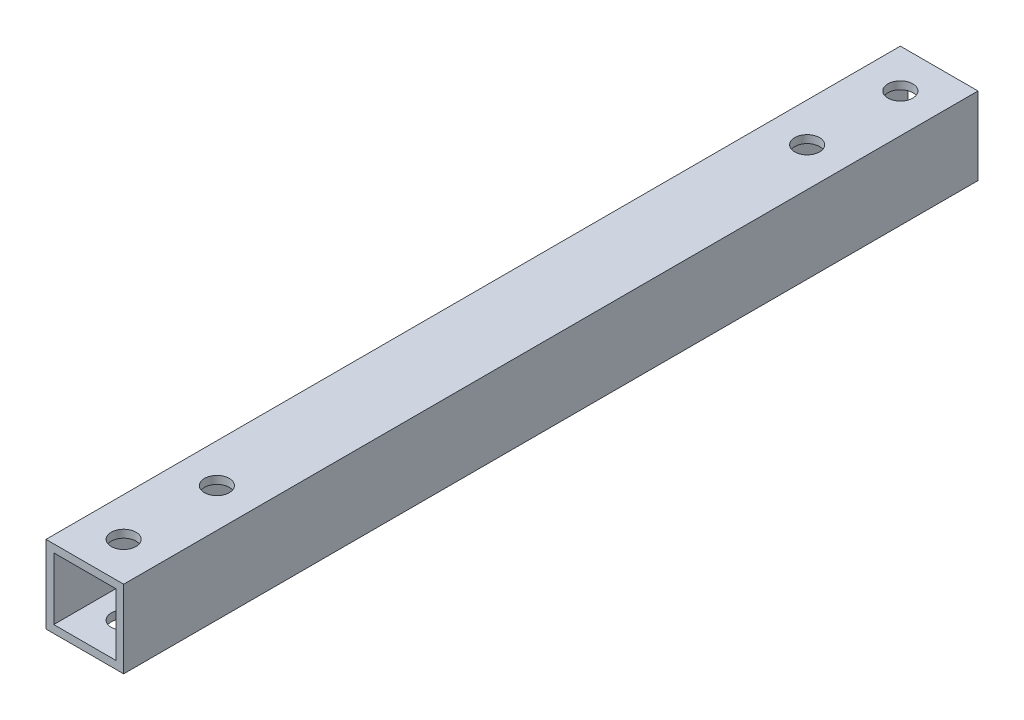
SolidWorks part; units mm, degrees
material "6061 合金"
ref_plane "正面" through (0, 0, 0) normal (0, 0, 1) x (1, 0, 0)
ref_plane "平面" through (0, 0, 0) normal (0, 1, 0) x (1, 0, 0)
ref_plane "右側面" through (0, 0, 0) normal (1, 0, 0) x (0, 0, -1)
sketch "断面 スケッチ" plane through (0, 0, 0) normal (0, 0, 1) x (1, 0, 0)
  line L1 (-5, -5) -> (5, -5)
  line L2 (-5, -5) -> (-5, 5)
  line L3 (-5, 5) -> (5, 5)
  line L4 (5, -5) -> (5, 5)
  line L5 (-5, -5) -> (5, 5) construction
  line L6 (-5, 5) -> (5, -5) construction
  point P0 (0, 0)
  dimension "D1" = 10
extrude "フレーム全長" add sketch "断面 スケッチ" along normal blind 110 thin thin type one direction reverse wall 1
sketch "上面穴 スケッチ" plane through (0, 5, 0) normal (0, 1, 0) x (1, 0, 0)
  line L0 (0, 0) -> (0, -110) construction
  line L1 (5, 0) -> (-5, 0) construction
  line L2 (5, -110) -> (-5, -110) construction
  line L3 (-5, -55) -> (5, -55) construction
  line L4 (-5, -110) -> (-5, 0) construction
  line L5 (5, -110) -> (5, 0) construction
  circle A0 centre (0, -5) radius 1.6
  circle A1 centre (0, -17) radius 1.6
  circle A2 centre (0, -93) radius 1.6
  circle A3 centre (0, -105) radius 1.6
  dimension "D1" = 5
  dimension "D2" = 3.2
  dimension "D3" = 12
sketch "側面穴 スケッチ" plane through (5, 0, 0) normal (1, 0, 0) x (0, 0, -1)
  line L0 (0, 0) -> (-110, 0) construction
  line L1 (0, -5) -> (0, 5) construction
  line L2 (-110, -5) -> (-110, 5) construction
  line L3 (-55, 5) -> (-55, -5) construction
  line L4 (-110, 5) -> (0, 5) construction
  line L5 (-110, -5) -> (0, -5) construction
  circle A0 centre (-15, 0) radius 1.6
  dimension "D1" = 15
  dimension "D2" = 3.2
extrude "上面穴貫通" cut sketch "上面穴 スケッチ" against normal through all
extrude "側面穴貫通" [suppressed] cut sketch "側面穴 スケッチ" against normal through all
fillet "フィレット" [suppressed] radius 5
